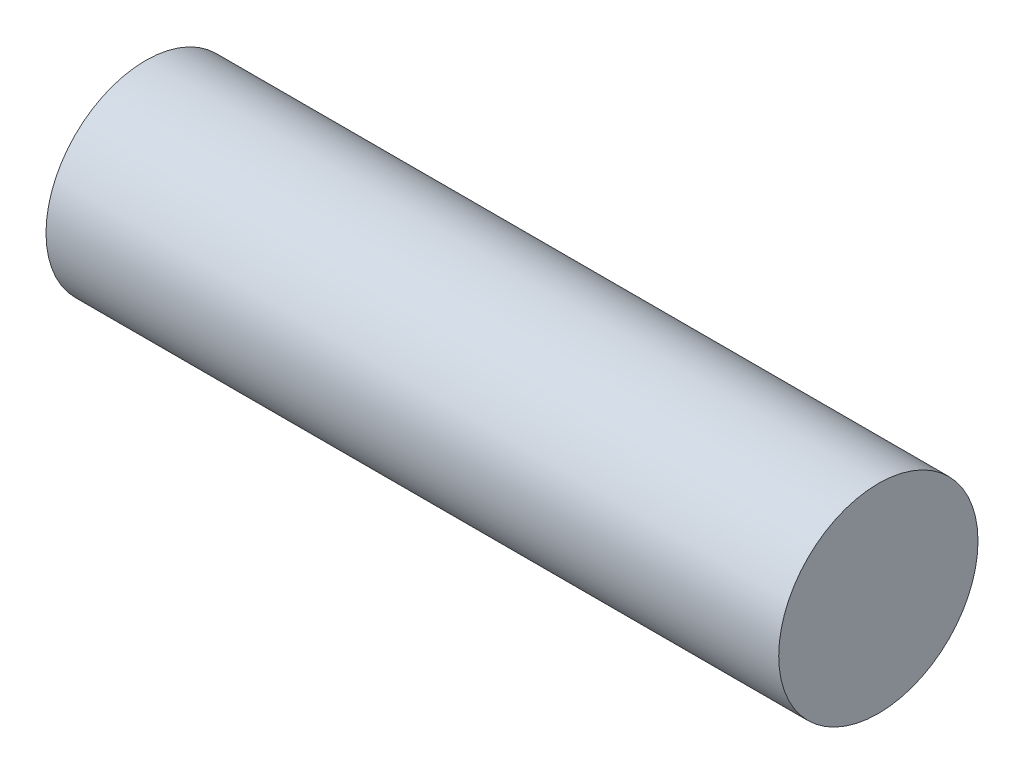
SolidWorks part; units mm, degrees
ref_plane "Front Plane" through (0, 0, 0) normal (0, 0, 1) x (1, 0, 0)
ref_plane "Top Plane" through (0, 0, 0) normal (0, 1, 0) x (1, 0, 0)
ref_plane "Right Plane" through (0, 0, 0) normal (1, 0, 0) x (0, 0, -1)
sketch "Sketch1" plane through (0, 0, 0) normal (1, 0, 0) x (0, 0, -1)
  circle A0 centre (0, 0) radius 34
  dimension "D1" = 68
extrude "Boss-Extrude1" add sketch "Sketch1" along normal blind 250
